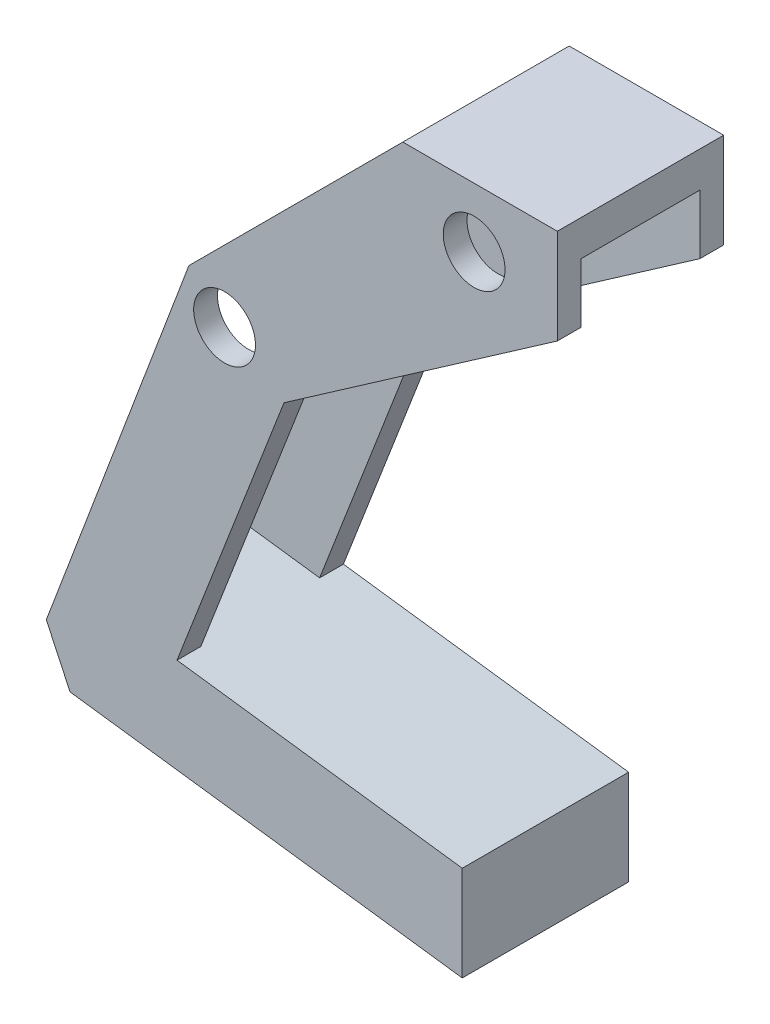
SolidWorks part; units mm, degrees
ref_plane "前视基准面" through (0, 0, 0) normal (0, 0, 1) x (1, 0, 0)
ref_plane "上视基准面" through (0, 0, 0) normal (0, 1, 0) x (1, 0, 0)
ref_plane "右视基准面" through (0, 0, 0) normal (1, 0, 0) x (0, 0, -1)
other "Configuration Table"
sketch "草图1" plane through (0, 0, 0) normal (0, 0, 1) x (1, 0, 0)
  line L0 (-12, 60) -> (-25, 60)
  line L1 (-25, 60) -> (-43, 42)
  line L2 (-43, 42) -> (-55, 10.1877)
  line L3 (-55, 10.1877) -> (-53, 5.9244)
  line L4 (-53, 5.9244) -> (-20, 1.5798)
  line L5 (-20, 1.5798) -> (-20, 9.5798)
  line L6 (-20, 9.5798) -> (-44, 12.7395)
  line L7 (-44, 12.7395) -> (-35, 36)
  line L8 (-35, 36) -> (-12, 52)
  line L9 (-12, 52) -> (-12, 60)
  dimension "x0" = 12
  dimension "x1" = 25
  dimension "x2" = 43
  dimension "x3" = 55
  dimension "x4" = 53
  dimension "x5" = 20
  dimension "x7" = 44
  dimension "x8" = 35
  dimension "y0" = 60
  dimension "y2" = 42
  dimension "y3" = 10.1877
  dimension "y4" = 5.9244
  dimension "y5" = 1.5798
  dimension "y6" = 9.5798
  dimension "y7" = 12.7395
  dimension "y8" = 36
  dimension "y9" = 52
extrude "Extrude" add sketch "草图1" along normal blind 14
ref_plane "Fork_midplane" through (0, 0, 7) normal (0, 0, 1) x (1, 0, 0)
sketch "草图3" plane through (0, 0, 7) normal (0, 0, 1) x (1, 0, 0)
  line L0 (5, 6.2885) -> (-65, 15.5042)
  line L1 (-65, 15.5042) -> (-65, 57)
  line L2 (-65, 57) -> (5, 57)
  line L3 (5, 57) -> (5, 6.2885)
  dimension "x0" = 5
  dimension "x1" = 65
  dimension "y0" = 6.2885
  dimension "y1" = 15.5042
  dimension "y2" = 57
extrude "Fork_above_mounting_foot" cut sketch "草图3" against normal mid plane 10
sketch "草图4" plane through (0, 0, 14) normal (0, 0, 1) x (1, 0, 0)
  circle A0 centre (-40, 39) radius 2.6
  dimension "diameter" = 5.2
  dimension "x" = 40
  dimension "y" = 39
extrude "Outer_pivot_bore" cut sketch "草图4" against normal through all
sketch "草图5" plane through (0, 0, 14) normal (0, 0, 1) x (1, 0, 0)
  circle A0 centre (-19, 55) radius 2.6
  dimension "diameter" = 5.2
  dimension "x" = 19
  dimension "y" = 55
extrude "Upper_hinge_bore" cut sketch "草图5" against normal through all
